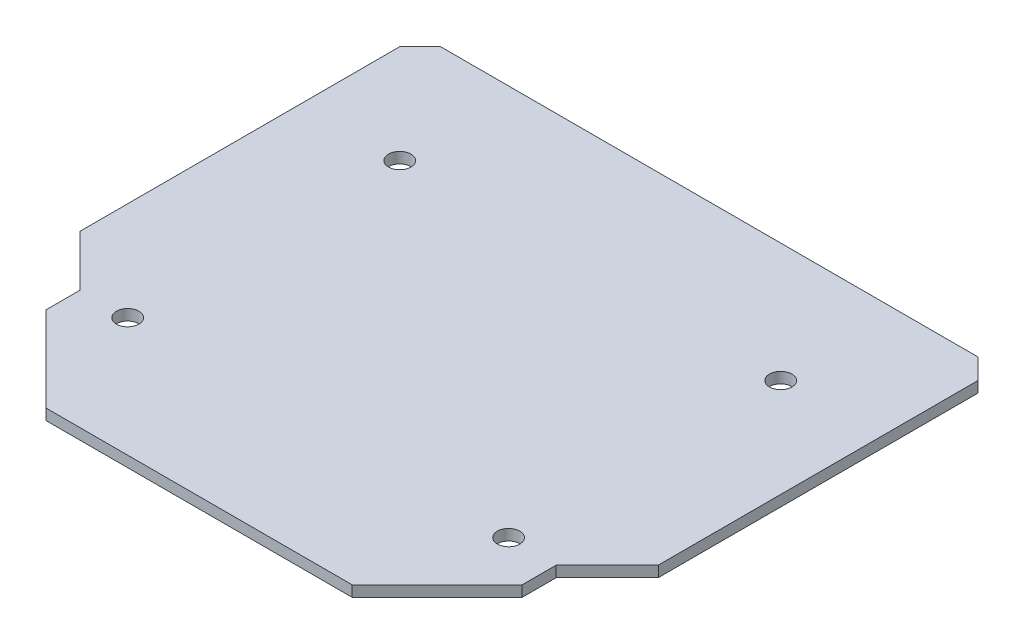
SolidWorks part; units mm, degrees
ref_plane "前视基准面" through (0, 0, 0) normal (0, 0, 1) x (1, 0, 0)
ref_plane "上视基准面" through (0, 0, 0) normal (0, 1, 0) x (1, 0, 0)
ref_plane "右视基准面" through (0, 0, 0) normal (1, 0, 0) x (0, 0, -1)
sketch "草图1" plane through (0, 0, 0) normal (0, 1, 0) x (1, 0, 0)
  line L1 (-42.5, -37.5) -> (42.5, -37.5)
  line L2 (-42.5, -37.5) -> (-42.5, 37.5)
  line L3 (-42.5, 37.5) -> (42.5, 37.5)
  line L4 (42.5, -37.5) -> (42.5, 37.5)
  line L5 (-42.5, -37.5) -> (42.5, 37.5) construction
  line L6 (-42.5, 37.5) -> (42.5, -37.5) construction
  point P0 (0, 0)
  dimension "D1" = 85
  dimension "D2" = 75
extrude "凸台-拉伸1" add sketch "草图1" along normal blind 1.6
sketch "草图2" plane through (0, 1.6, 0) normal (0, 1, 0) x (1, 0, 0)
  line L1 (-28, -20) -> (28, -20) construction
  line L2 (-28, -20) -> (-28, 20) construction
  line L3 (-28, 20) -> (28, 20) construction
  line L4 (28, -20) -> (28, 20) construction
  line L5 (-28, -20) -> (28, 20) construction
  line L6 (-28, 20) -> (28, -20) construction
  circle A0 centre (-28, 20) radius 1.65
  circle A1 centre (-28, -20) radius 1.65
  circle A2 centre (28, 20) radius 1.65
  circle A3 centre (28, -20) radius 1.65
  point P0 (0, 0)
  dimension "D3" = 3.3
  dimension "D1" = 56
  dimension "D2" = 40
extrude "切除-拉伸1" cut sketch "草图2" against normal up to next
chamfer "倒角2" distance 3 angle 45 2 edges at (42.5, 0.8, -37.5) (-42.5, 0.8, -37.5)
chamfer "倒角3" distance 20 angle 45 2 edges at (42.5, 0.8, 37.5) (-42.5, 0.8, 37.5)
sketch "草图7" plane through (0, 1.6, 0) normal (0, 1, 0) x (1, 0, 0)
  line L0 (-35, -25) -> (-35, -20)
  line L1 (-42.5, -17.5) -> (-22.5, -37.5) construction
  line L2 (-35, -20) -> (-42.5, -12.5)
  line L3 (-42.5, 34.5) -> (-42.5, -17.5) construction
  line L4 (-42.5, -12.5) -> (-42.5, -17.5)
  line L5 (-42.5, -17.5) -> (-35, -25)
  dimension "D1" = 5
  dimension "D2" = 7.5
extrude "切除-拉伸4" cut sketch "草图7" against normal up to next
mirror "镜向1" about plane through (0, 0, 0) normal (1, 0, 0) of "切除-拉伸4"
